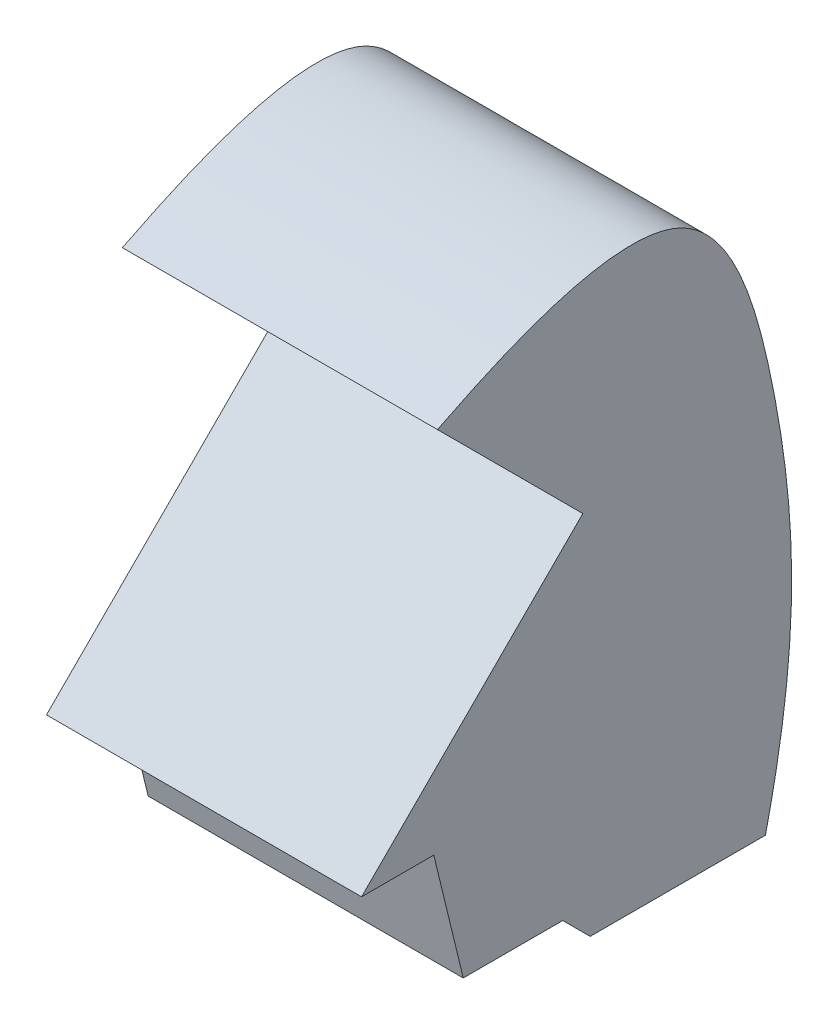
SolidWorks part; units mm, degrees
ref_plane "Front Plane" through (0, 0, 0) normal (0, 0, 1) x (1, 0, 0)
ref_plane "Top Plane" through (0, 0, 0) normal (0, 1, 0) x (1, 0, 0)
ref_plane "Right Plane" through (0, 0, 0) normal (1, 0, 0) x (0, 0, -1)
sketch "Sketch2" plane through (0, 0, 0) normal (1, 0, 0) x (0, 0, -1)
  line L0 (0, 0) -> (0, 96.668) construction
  line L1 (-32.9848, 37.1569) -> (-21.9105, 26.0826)
  line L2 (-21.9105, 26.0826) -> (-38.7649, 9.2282)
  line L3 (-38.7649, 9.2282) -> (-33.2642, 9.2282)
  line L4 (-33.2642, 9.2282) -> (-31.0198, 0)
  line L5 (-31.0198, 0) -> (-23.4409, 0)
  line L6 (-23.4409, 0) -> (-21.3497, -2.0911)
  line L7 (-21.3497, -2.0911) -> (-8.0022, -2.0911)
  spline S0 degree 3 poles (-32.9848, 37.1569) (-28.5974, 39.3515) (-12.6543, 47.0611) (-5.1918, 21.1203) (-5.564, 8.3987) (-8.0022, -2.0911) knots 0 0 0 0 0.297118 0.535651 1 1 1 1
ref_plane "Plane1" through (-6, 0, 0) normal (1, 0, 0) x (0, 0, -1)
extrude "Boss-Extrude1" add sketch "Sketch2" against normal blind 24 contours L2 L3 L4 L5 L6 L7 S0 L1
ref_plane "Plane2" through (0, 1.1482, -4.7211) normal (0, 0.2363, -0.9717) x (-1, 0, 0)
sketch "Sketch11" plane through (0, 1.1482, -4.7211) normal (0, 0.2363, -0.9717) x (-1, 0, 0)
  circle A0 centre (11.6644, 22.3586) radius 5.6978
extrude "Cut-Extrude4" cut sketch "Sketch11" against normal blind 7
ref_plane "Plane5" through (0, -0.2697, 1.1089) normal (0, -0.2363, 0.9717) x (1, 0, 0)
sketch "Sketch67" plane through (0, -0.2697, 1.1089) normal (0, -0.2363, 0.9717) x (1, 0, 0)
  line L0 (-11.6644, 22.3586) -> (-11.6644, 37.1437) construction
  line L1 (-11.6644, 22.3586) -> (-11.6644, 16.3853) construction
  line L2 (-11.6644, 16.3853) -> (-11.6644, 15.6846) construction
  line L3 (-11.6644, 29.1068) -> (-11.6644, 16.0349)
  spline S0 degree 3 poles (-9.952, 28.8486) (-5.7427, 26.3092) (-2.2406, 18.7624) (-10.25, 16.3853) knots 0 0 0 0 1 1 1 1
  spline S1 degree 2 poles (-9.952, 28.8486) (-10.7751, 29.2126) (-11.6644, 29.1068) knots 0 0 0 1 1 1
  spline S2 degree 2 poles (-10.25, 16.3853) (-10.9367, 16.1236) (-11.6644, 16.0349) knots 0 0 0 1 1 1
revolve "Revolve1" add sketch "Sketch67" angle 360 about L0
scale "Scale1" bodies to scale 106 scale about origin uniform scaling yes scale factor 10
